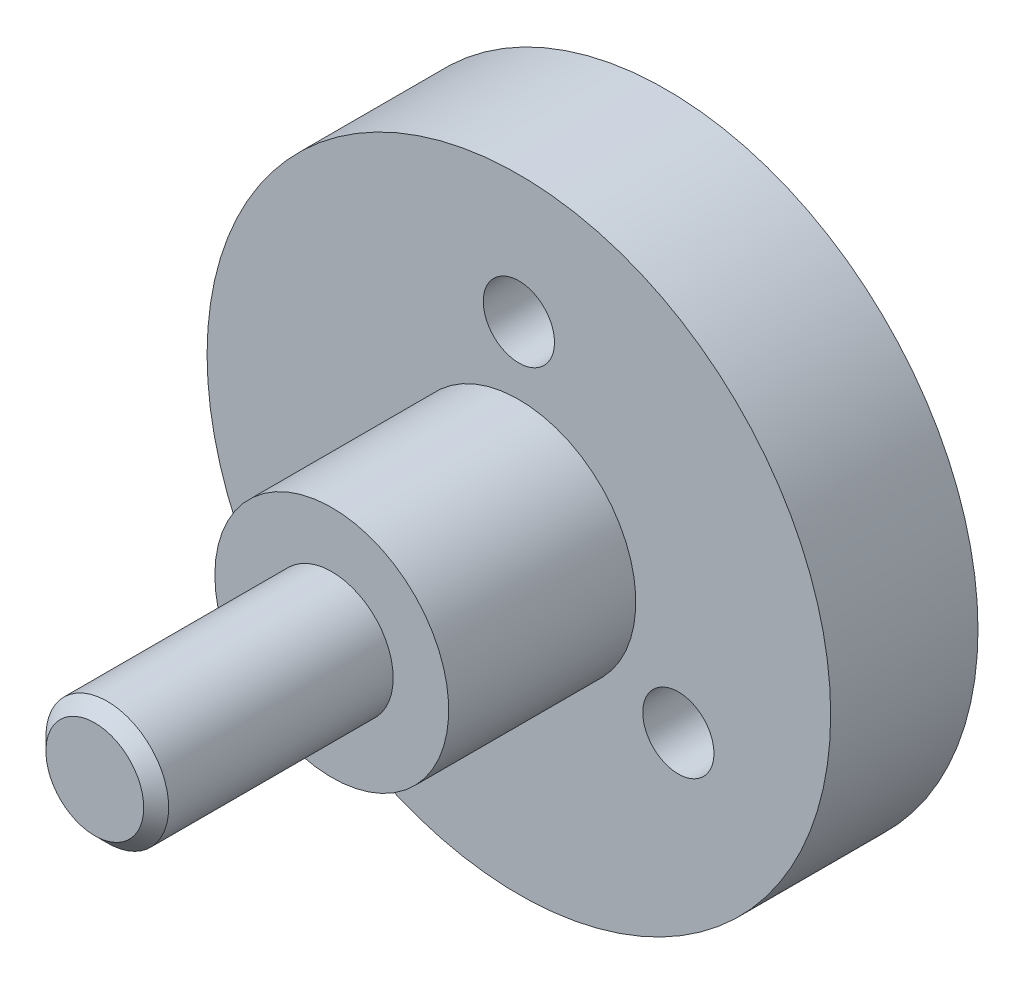
SolidWorks part; units mm, degrees
material "6061 Alloy"
ref_plane "Front Plane" through (0, 0, 0) normal (0, 0, 1) x (1, 0, 0)
ref_plane "Top Plane" through (0, 0, 0) normal (0, 1, 0) x (1, 0, 0)
ref_plane "Right Plane" through (0, 0, 0) normal (1, 0, 0) x (0, 0, -1)
sketch "Sketch1" plane through (0, 0, 0) normal (0, 0, 1) x (1, 0, 0)
  circle A0 centre (0, 0) radius 12.7
  dimension "D2" = 25.4
extrude "Mounting Flange" add sketch "Sketch1" along normal blind 6
sketch "Sketch2" plane through (0, 0, 6) normal (0, 0, 1) x (1, 0, 0)
  circle A0 centre (0, 0) radius 2.5
  dimension "D1" = 5
sketch "Sketch3" plane through (0, 0, 0) normal (0, 0, -1) x (-1, 0, 0)
  circle A0 centre (0, 0) radius 6.35
  dimension "D1" = 12.7
extrude "Motor Shaft Relief" cut sketch "Sketch3" against normal blind 2.54
sketch "Sketch4" plane through (0, 0, 6) normal (0, 0, 1) x (1, 0, 0)
  circle A0 centre (0, 0) radius 7.5 construction
  circle A1 centre (0, 7.5) radius 1.45
  circle A2 centre (6.4952, -3.75) radius 1.45
  circle A3 centre (-6.4952, -3.75) radius 1.45
  point P11 (0, 0)
  dimension "D1" = 15
  dimension "D2" = 2.9
  dimension "D4" = 120
  dimension "D5" = 120
  dimension "D3" = 3
extrude "Screw Clearance Holes" cut sketch "Sketch4" against normal through all
extrude "Drive Shaft" add sketch "Sketch2" along normal blind 17.272 contours A0
chamfer "Chamfer1" distance 0.508 angle 45 1 edges at (2.5, 0, 23.272)
sketch "Sketch5" plane through (0, 0, 6) normal (0, 0, 1) x (1, 0, 0)
  circle A0 centre (0, 0) radius 4.7625
  dimension "D1" = 9.525
extrude "Shaft Support Shoulder" add sketch "Sketch5" along normal blind 7.62
